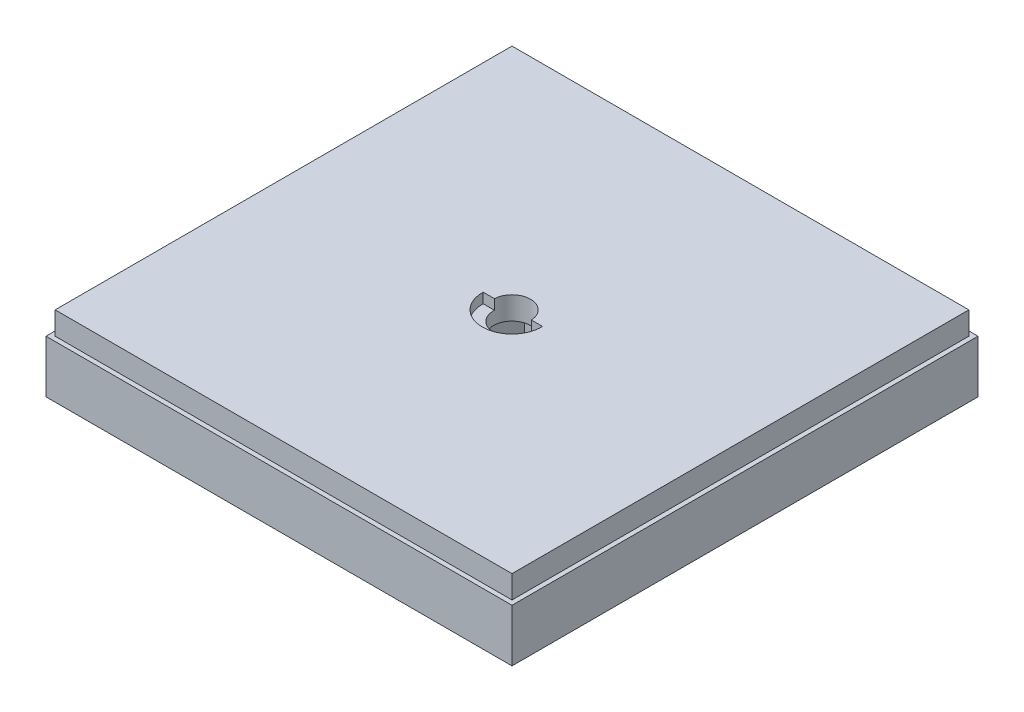
SolidWorks part; units mm, degrees
ref_plane "Front Plane" through (0, 0, 0) normal (0, 0, 1) x (1, 0, 0)
ref_plane "Top Plane" through (0, 0, 0) normal (0, 1, 0) x (1, 0, 0)
ref_plane "Right Plane" through (0, 0, 0) normal (1, 0, 0) x (0, 0, -1)
sketch "Sketch1" plane through (0, 0, 0) normal (0, 1, 0) x (1, 0, 0)
  line L0 (-102, 102) -> (0, 0) construction
  line L1 (-102, 102) -> (0, 102)
  line L2 (-102, 102) -> (-102, 0)
  line L3 (-102, 0) -> (0, 0)
  line L4 (0, 102) -> (0, 0)
  line L6 (-43.4944, 51) -> (-47.2472, 57.5)
  line L7 (-47.2472, 57.5) -> (-54.7528, 57.5)
  line L8 (-54.7528, 57.5) -> (-58.5056, 51)
  line L9 (-58.5056, 51) -> (-54.7528, 44.5)
  line L10 (-54.7528, 44.5) -> (-47.2472, 44.5)
  line L11 (-47.2472, 44.5) -> (-43.4944, 51)
  circle A0 centre (-51, 51) radius 6.5 construction
  dimension "D1" = 102
  dimension "D2" = 102
  dimension "D3" = 13
extrude "Boss-Extrude1" add sketch "Sketch1" along normal blind 11.5
sketch "Sketch2" plane through (0, 11.5, 0) normal (0, 1, 0) x (1, 0, 0)
  line L4 (-101, 101) -> (-1, 1) construction
  line L8 (-101, 101) -> (-101, 1)
  line L9 (-101, 1) -> (-1, 1)
  line L10 (-1, 1) -> (-1, 101)
  line L11 (-1, 101) -> (-101, 101)
  line L12 (-101, 101) -> (-101, 1)
  line L13 (-101, 1) -> (-1, 1)
  line L14 (-1, 1) -> (-1, 101)
  line L15 (-1, 101) -> (-101, 101)
  circle A0 centre (-51, 51) radius 4.05
  dimension "8.1" = 8.1
  dimension "D1" = 1
extrude "Boss-Extrude2" add sketch "Sketch2" along normal blind 5
sketch "Sketch3" plane through (0, 0, 0) normal (0, -1, 0) x (1, 0, 0)
  circle A0 centre (-51, -51) radius 8
  dimension "D1" = 16
extrude "Cut-Extrude1" cut sketch "Sketch3" against normal blind 7
sketch "Sketch4" plane through (0, 16.5, 0) normal (0, 1, 0) x (1, 0, 0)
  line L0 (-32.5, 51) -> (-19.5, 51) construction
  line L1 (-57.4969, 51.2) -> (-44.5031, 51.2)
  arc A0 (-57.4969, 51.2) -> (-44.5031, 51.2) centre (-51, 51) ccw
  dimension "D1" = 13
  dimension "D2" = 0.2
extrude "Cut-Extrude2" cut sketch "Sketch4" against normal blind 2.2
